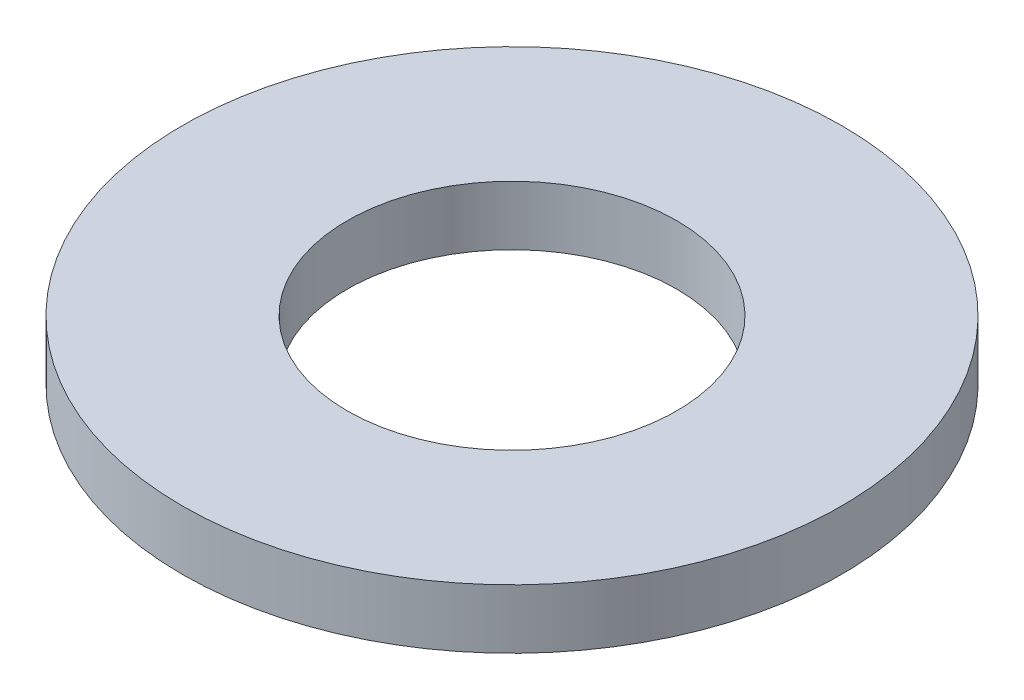
SolidWorks part; units mm, degrees
ref_plane "Спереди" through (0, 0, 0) normal (0, 0, 1) x (1, 0, 0)
ref_plane "Сверху" through (0, 0, 0) normal (0, 1, 0) x (1, 0, 0)
ref_plane "Справа" through (0, 0, 0) normal (1, 0, 0) x (0, 0, -1)
sketch "Эскиз1" plane through (0, 0, 0) normal (0, 1, 0) x (1, 0, 0)
  circle A0 centre (0, 0) radius 10
  circle A1 centre (0, 0) radius 5
  dimension "D1" = 10
  dimension "D2" = 20
extrude "Бобышка-Вытянуть1" add sketch "Эскиз1" along normal blind 1.8
